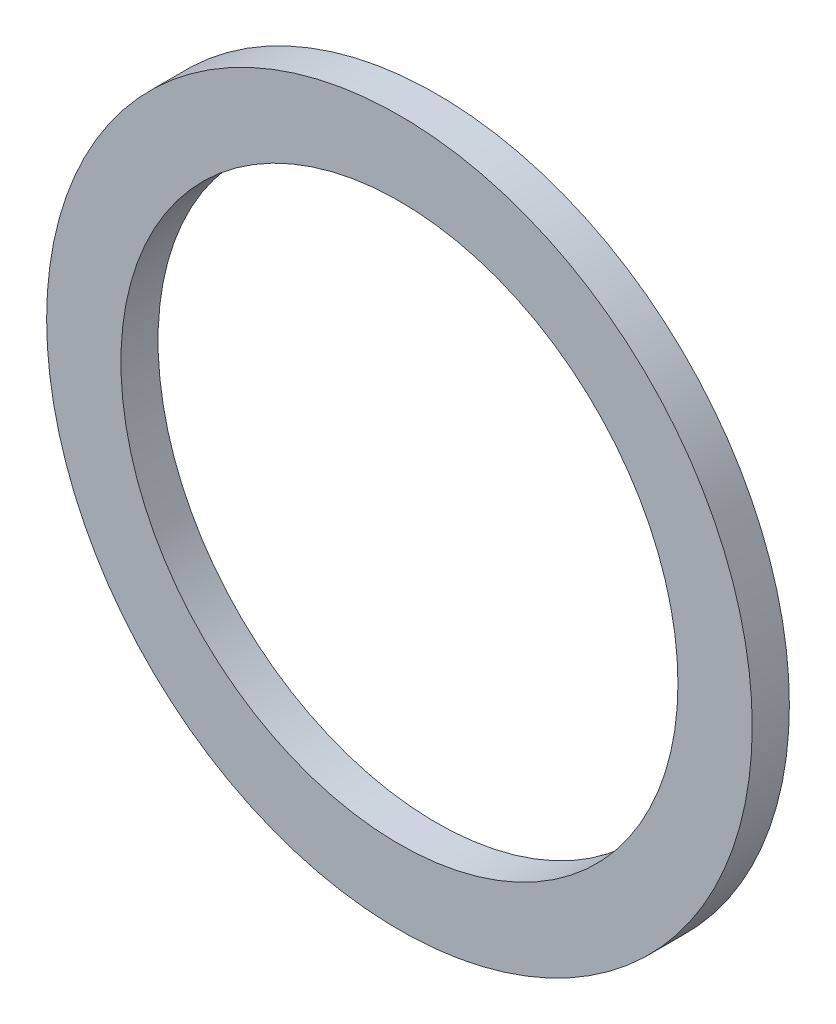
SolidWorks part; units mm, degrees
ref_plane "Plan de face" through (0, 0, 0) normal (0, 0, 1) x (1, 0, 0)
ref_plane "Plan de dessus" through (0, 0, 0) normal (0, 1, 0) x (1, 0, 0)
ref_plane "Plan de droite" through (0, 0, 0) normal (1, 0, 0) x (0, 0, -1)
sketch "Esquisse1" plane through (0, 0, 0) normal (0, 0, 1) x (1, 0, 0)
  circle A0 centre (0, 0) radius 19
  circle A1 centre (0, 0) radius 15
  dimension "D1" = 30
  dimension "D2" = 38
extrude "Extrusion1" add sketch "Esquisse1" along normal blind 2
